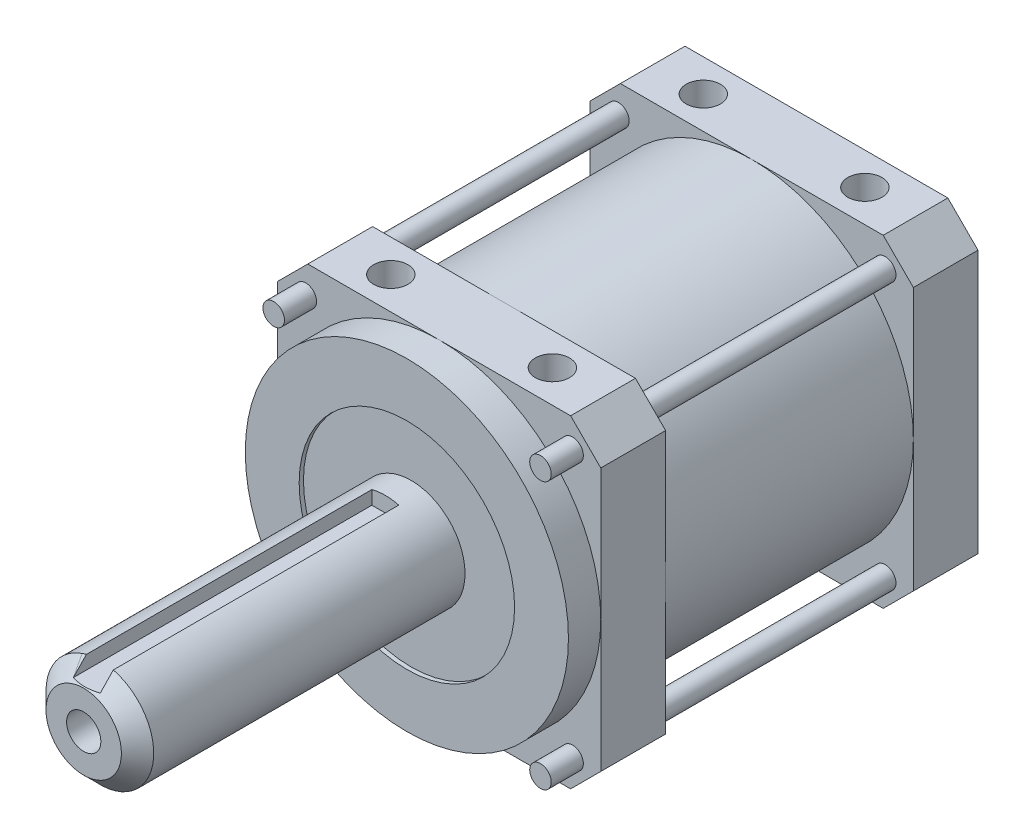
SolidWorks part; units mm, degrees
ref_plane "Front Plane" through (0, 0, 0) normal (0, 0, 1) x (1, 0, 0)
ref_plane "Top Plane" through (0, 0, 0) normal (0, 1, 0) x (1, 0, 0)
ref_plane "Right Plane" through (0, 0, 0) normal (1, 0, 0) x (0, 0, -1)
sketch "Sketch1" plane through (0, 0, 0) normal (0, 0, 1) x (1, 0, 0)
  line L1 (-19.05, -19.05) -> (19.05, -19.05)
  line L2 (-19.05, -19.05) -> (-19.05, 19.05)
  line L3 (-19.05, 19.05) -> (19.05, 19.05)
  line L4 (19.05, -19.05) -> (19.05, 19.05)
  line L5 (-19.05, -19.05) -> (19.05, 19.05) construction
  line L6 (-19.05, 19.05) -> (19.05, -19.05) construction
  point P0 (0, 0)
  dimension "D1" = 38.1
  dimension "D2" = 38.1
extrude "Boss-Extrude1" add sketch "Sketch1" along normal blind 7.62
chamfer "Chamfer1" distance 3.556 angle 45 4 edges at (19.05, -19.05, 3.81) (-19.05, -19.05, 3.81) (-19.05, 19.05, 3.81) (19.05, 19.05, 3.81)
sketch "Sketch2" plane through (0, 0, 7.62) normal (0, 0, 1) x (1, 0, 0)
  circle A0 centre (0, 0) radius 19.05
  dimension "D1" = 38.1
extrude "Boss-Extrude2" add sketch "Sketch2" along normal blind 29.21
sketch "Sketch3" plane through (0, 0, 36.83) normal (0, 0, 1) x (1, 0, 0)
  line L1 (19.05, -19.05) -> (-19.05, -19.05)
  line L2 (19.05, -19.05) -> (19.05, 19.05)
  line L3 (19.05, 19.05) -> (-19.05, 19.05)
  line L4 (-19.05, -19.05) -> (-19.05, 19.05)
  line L5 (19.05, -19.05) -> (-19.05, 19.05) construction
  line L6 (19.05, 19.05) -> (-19.05, -19.05) construction
  point P0 (0, 0)
  dimension "D1" = 38.1
extrude "Boss-Extrude3" add sketch "Sketch3" along normal blind 7.6454
chamfer "Chamfer2" distance 3.556 angle 45 1 edges at (19.05, 19.05, 40.6527)
sketch "Sketch4" plane through (0, 0, 0) normal (0, 0, -1) x (-1, 0, 0)
  line L0 (0, 0) -> (0, 13.9862) construction
  line L1 (0, 0) -> (-30.3045, 0) construction
  line L2 (-15.494, 19.05) -> (-19.05, 15.494) construction
  circle A0 centre (-15.7274, 15.7274) radius 1.27
  circle A1 centre (15.7274, 15.7274) radius 1.27
  circle A2 centre (15.7274, -15.7274) radius 1.27
  circle A3 centre (-15.7274, -15.7274) radius 1.27
  dimension "D1" = 2.1844
  dimension "D2" = 2.54
extrude "Boss-Extrude4" add sketch "Sketch4" against normal blind 48.26
sketch "Sketch5" plane through (0, 0, 48.26) normal (0, 0, 1) x (1, 0, 0)
  circle A0 centre (15.7274, 15.7274) radius 2.7813
  circle A1 centre (-15.7274, 15.7274) radius 2.7813
  circle A2 centre (-15.7274, -15.7274) radius 2.7813
  circle A3 centre (15.7274, -15.7274) radius 2.7813
  dimension "D1" = 5.5626
  dimension "D2" = 5.5626
  dimension "D3" = 5.5626
  dimension "D4" = 5.5626
sketch "Sketch6" plane through (0, 0, 44.4754) normal (0, 0, 1) x (1, 0, 0)
  circle A0 centre (0, 0) radius 19.05
  dimension "D1" = 38.1
extrude "Boss-Extrude6" add sketch "Sketch6" along normal blind 3.81
sketch "Sketch7" plane through (0, 0, 48.2854) normal (0, 0, 1) x (1, 0, 0)
  circle A0 centre (0, 0) radius 6.35
  dimension "D1" = 12.7
extrude "Boss-Extrude7" add sketch "Sketch7" along normal blind 38.1
chamfer "Chamfer3" distance 1.905 angle 45 1 edges at (6.35, 0, 86.3854)
sketch "Sketch8" plane through (0, 0, 48.2854) normal (0, 0, 1) x (1, 0, 0)
  circle A0 centre (0, 0) radius 6.35
  circle A1 centre (0, 0) radius 12.7
  circle A2 centre (0, 0) radius 19.05 construction
  dimension "D1" = 6.35
extrude "Cut-Extrude2" cut sketch "Sketch8" against normal blind 0.508
sketch "Sketch9" plane through (0, 19.05, 0) normal (0, 1, 0) x (1, 0, 0)
  line L0 (15.494, -40.6527) -> (-15.494, -40.6527) construction
  line L2 (15.494, -44.4754) -> (15.494, -36.83) construction
  line L3 (-15.494, -36.83) -> (-15.494, -44.4754) construction
  line L4 (0, -40.6527) -> (0, -62.2116) construction
  line L5 (19.05, -36.83) -> (19.05, -44.4754) construction
  point P6 (9.525, -40.6527)
  point P10 (-9.525, -40.6527)
  dimension "D1" = 9.525
sketch "Sketch10" plane through (0, 0, 86.3854) normal (0, 0, 1) x (1, 0, 0)
  point P0 (0, 0)
hole_wizard "#10-32 Tapped Hole1" positions "3DSketch1" profile "Sketch11" tap size "#10-32" standard "ANSI Inch"
sketch3d "3DSketch1"
  point P0 (0, 0, 86.3854)
sketch "Sketch11" plane through (0, 0, 86.3854) normal (1, 0, 0) x (0, -1, 0)
  line L0 (0, 0) -> (0, 14.4213)
  line L1 (0, 14.4213) -> (2.0193, 13.208)
  line L2 (2.0193, 13.208) -> (2.0193, 0)
  line L5 (2.0193, 0) -> (0, 0)
  line L10 (0, 14.4213) -> (-2.0193, 13.208) construction
  line L11 (0, -6.35) -> (0, 107.95) construction
  dimension "Tap Drill Dia." = 4.0386
  dimension "Tap Drill Depth" = 13.208
  dimension "Drill Angle" = 118
cosmetic thread "Hole Thread1" parameters "D1"=12.7, "D2"=5.0038
hole_wizard "#10-32 Tapped Hole2" positions "3DSketch2" profile "Sketch14" tap size "#10-32" standard "ANSI Inch"
sketch3d "3DSketch2"
  point P0 (9.525, 19.05, 40.6527)
  point P3 (-9.525, 19.05, 40.6527)
sketch "Sketch14" plane through (9.525, 19.05, 40.6527) normal (1, 0, 0) x (0, 0, 1)
  line L0 (0, 0) -> (0, 11.3733)
  line L1 (0, 11.3733) -> (2.0193, 10.16)
  line L2 (2.0193, 10.16) -> (2.0193, 0)
  line L5 (2.0193, 0) -> (0, 0)
  line L10 (0, 11.3733) -> (-2.0193, 10.16) construction
  line L11 (0, -6.35) -> (0, 107.95) construction
  dimension "Tap Drill Dia." = 4.0386
  dimension "Tap Drill Depth" = 10.16
  dimension "Drill Angle" = 118
cosmetic thread "Hole Thread2" parameters "D1"=10.16, "D2"=4.826
cosmetic thread "Hole Thread3" parameters "D1"=10.16, "D2"=4.826
sketch "Sketch15" plane through (0, 19.05, 0) normal (0, 1, 0) x (1, 0, 0)
  line L0 (15.494, -3.81) -> (-15.494, -3.81) construction
  line L1 (15.494, -7.62) -> (15.494, 0) construction
  line L2 (-15.494, 0) -> (-15.494, -7.62) construction
  line L3 (0, -3.81) -> (0, -26.697) construction
  point P6 (9.525, -3.81)
  point P12 (-9.525, -3.81)
hole_wizard "#10-32 Tapped Hole3" positions "Sketch16" profile "Sketch17" tap size "#10-32" standard "ANSI Inch"
sketch "Sketch16" plane through (0, 19.05, 0) normal (0, 1, 0) x (1, 0, 0)
  point P0 (9.525, -3.81)
  point P3 (-9.525, -3.81)
sketch "Sketch17" plane through (9.525, 19.05, 3.81) normal (1, 0, 0) x (0, 0, 1)
  line L0 (0, 0) -> (0, 12.6433)
  line L1 (0, 12.6433) -> (2.0193, 11.43)
  line L2 (2.0193, 11.43) -> (2.0193, 0)
  line L5 (2.0193, 0) -> (0, 0)
  line L10 (0, 12.6433) -> (-2.0193, 11.43) construction
  line L11 (0, -6.35) -> (0, 107.95) construction
  dimension "Tap Drill Dia." = 4.0386
  dimension "Tap Drill Depth" = 11.43
  dimension "Drill Angle" = 118
cosmetic thread "Hole Thread4" parameters "D1"=9.144, "D2"=4.826
cosmetic thread "Hole Thread5" parameters "D1"=9.144, "D2"=4.826
ref_plane "Plane3" through (0, 0, 0) normal (0, 1, 0) x (1, 0, 0)
mirror "Mirror1" about plane through (0, 0, 0) normal (0, 1, 0) of "#10-32 Tapped Hole3", "#10-32 Tapped Hole2"
sketch "Sketch19" plane through (0, 0, 86.3854) normal (0, 0, 1) x (1, 0, 0)
  line L1 (-1.5875, 4.5466) -> (1.5875, 4.5466)
  line L2 (-1.5875, 4.5466) -> (-1.5875, 8.1534)
  line L3 (-1.5875, 8.1534) -> (1.5875, 8.1534)
  line L4 (1.5875, 4.5466) -> (1.5875, 8.1534)
  line L5 (-1.5875, 4.5466) -> (1.5875, 8.1534) construction
  line L6 (-1.5875, 8.1534) -> (1.5875, 4.5466) construction
  circle A0 centre (0, 0) radius 6.35 construction
  point P0 (0, 6.35)
  dimension "D1" = 3.175
  dimension "D2" = 3.6068
extrude "Cut-Extrude4" cut sketch "Sketch19" against normal blind 35.56
sketch "Sketch20" plane through (0, 0, 0) normal (0, 0, -1) x (-1, 0, 0)
  circle A0 centre (0, 0) radius 4.9022
  circle A1 centre (0, 0) radius 7.6708
  circle A2 centre (0, 7.6708) radius 1.4986
  circle A3 centre (0, -7.6708) radius 1.4986
  dimension "D1" = 9.8044
  dimension "D2" = 15.3416
  dimension "D3" = 2.9972
  dimension "D4" = 2.9972
sketch "Sketch23" plane through (-19.05, 0, 0) normal (-1, 0, 0) x (0, 0, 1)
  circle A0 centre (3.6717, 16.2247) radius 1.7381
extrude "Cut-Extrude5" cut sketch "Sketch20" against normal blind 5.08 contours A0 | A1 A2 | A1 A2 | A1 A3 | A1 A3
